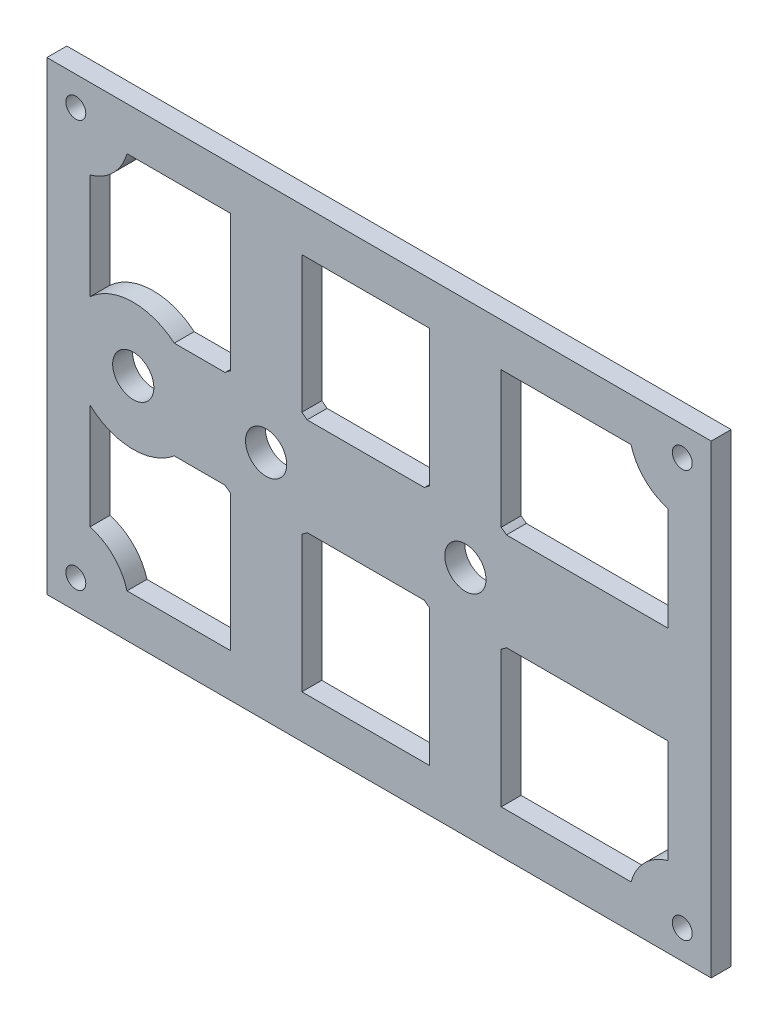
SolidWorks part; units mm, degrees
ref_plane "Front Plane" through (0, 0, 0) normal (0, 0, 1) x (1, 0, 0)
ref_plane "Top Plane" through (0, 0, 0) normal (0, 1, 0) x (1, 0, 0)
ref_plane "Right Plane" through (0, 0, 0) normal (1, 0, 0) x (0, 0, -1)
sketch "Sketch1" plane through (0, 0, 0) normal (0, 0, 1) x (1, 0, 0)
  line L1 (50, -35) -> (-50, -35)
  line L2 (50, -35) -> (50, 35)
  line L3 (50, 35) -> (-50, 35)
  line L4 (-50, -35) -> (-50, 35)
  line L5 (50, -35) -> (-50, 35) construction
  line L6 (50, 35) -> (-50, -35) construction
  point P0 (0, 0)
  dimension "D1" = 70
  dimension "D2" = 100
extrude "Boss-Extrude1" add sketch "Sketch1" along normal blind 3
sketch "Sketch2" plane through (0, 0, 3) normal (0, 0, 1) x (1, 0, 0)
  line L0 (-50, 35) -> (-50, -35) construction
  circle A0 centre (-17, 0) radius 3.1
  circle A1 centre (-37, 0) radius 3.1
  circle A2 centre (13, 0) radius 3.1
  dimension "D1" = 6.2
  dimension "D2" = 20
  dimension "D3" = 30
  dimension "D4" = 13
extrude "Cut-Extrude1" cut sketch "Sketch2" against normal through all
sketch "Sketch3" plane through (0, 0, 3) normal (0, 0, 1) x (1, 0, 0)
  line L0 (-50, 35) -> (-36.9943, 21.9943) construction
  circle A0 centre (-45.6446, 30.6446) radius 1.5
  dimension "D1" = 3
extrude "Cut-Extrude2" cut sketch "Sketch3" against normal through all
mirror "Mirror1" about plane through (0, 0, 0) normal (1, 0, 0) of "Cut-Extrude2"
mirror "Mirror2" about plane through (0, 0, 0) normal (0, 1, 0) of "Mirror1", "Cut-Extrude2"
sketch "Sketch4" plane through (0, 0, 3) normal (0, 0, 1) x (1, 0, 0)
  line L0 (7.6134, 28.5) -> (-11.6134, 28.5)
  line L1 (43.5, 7.3498) -> (43.5, 22.9374)
  line L2 (19.1758, -7.3498) -> (43.5, -7.3498)
  line L3 (18.3866, -28.5) -> (37.9374, -28.5)
  line L4 (-22.3866, 28.5) -> (-37.9374, 28.5)
  line L8 (-43.5, 28.5) -> (-43.5, -28.5)
  line L9 (-43.5, -28.5) -> (43.5, -28.5)
  line L10 (43.5, -28.5) -> (43.5, 28.5)
  line L11 (43.5, 28.5) -> (-43.5, 28.5)
  line L12 (-43.5, 22.9374) -> (-43.5, 7.0647)
  line L13 (-37.9374, -28.5) -> (-22.3866, -28.5)
  line L14 (43.5, -22.9374) -> (43.5, -7.3498)
  line L15 (37.9374, 28.5) -> (18.3866, 28.5)
  line L17 (-11.6134, -28.5) -> (7.6134, -28.5)
  line L18 (-17, 33.7741) -> (-17, -30.6446) construction
  line L20 (-11.6134, -28.5) -> (-11.6134, -7.9464)
  line L22 (-22.3866, -28.5) -> (-22.3866, -7.9464)
  line L23 (13, 30.6446) -> (13, -30.6446) construction
  line L24 (-46.714, 0) -> (46.9945, 0) construction
  line L26 (18.3866, -28.5) -> (18.3866, -7.9464)
  line L28 (7.6134, -28.5) -> (7.6134, -7.9464)
  line L29 (-43.5, -7.0647) -> (-43.5, -22.9374)
  line L30 (-10.8242, -7.3498) -> (6.8242, -7.3498)
  line L31 (-30.8242, 7.3498) -> (-23.1758, 7.3498)
  line L33 (-30.8242, -7.3498) -> (-23.1758, -7.3498)
  line L36 (-22.3866, 7.9464) -> (-22.3866, 28.5)
  line L37 (-11.6134, 7.9464) -> (-11.6134, 28.5)
  line L38 (-10.8242, 7.3498) -> (6.8242, 7.3498)
  line L40 (7.6134, 7.9464) -> (7.6134, 28.5)
  line L43 (18.3866, 7.9464) -> (18.3866, 28.5)
  line L44 (19.1758, 7.3498) -> (43.5, 7.3498)
  arc A0 (18.3866, -7.9464) -> (19.1758, -7.3498) centre (13, 0) ccw
  arc A1 (-23.1758, -7.3498) -> (-22.3866, -7.9464) centre (-17, 0) ccw
  arc A2 (-11.6134, -7.9464) -> (-10.8242, -7.3498) centre (-17, 0) ccw
  circle A3 centre (-45.6446, 30.6446) radius 8
  arc A4 (-43.5, 22.9374) -> (-37.9374, 28.5) centre (-45.6446, 30.6446) ccw
  arc A5 (-30.8242, 7.3498) -> (-43.5, 7.0647) centre (-37, 0) ccw
  circle A6 centre (-37, 0) radius 9.6
  arc A8 (-43.5, -7.0647) -> (-30.8242, -7.3498) centre (-37, 0) ccw
  circle A12 centre (-17, 0) radius 9.6
  arc A13 (-22.3866, 7.9464) -> (-23.1758, 7.3498) centre (-17, 0) ccw
  circle A15 centre (13, 0) radius 9.6
  arc A16 (6.8242, -7.3498) -> (7.6134, -7.9464) centre (13, 0) ccw
  circle A18 centre (45.6446, -30.6446) radius 8
  arc A19 (43.5, -22.9374) -> (37.9374, -28.5) centre (45.6446, -30.6446) ccw
  arc A20 (-10.8242, 7.3498) -> (-11.6134, 7.9464) centre (-17, 0) ccw
  circle A21 centre (45.6446, 30.6446) radius 8
  arc A22 (37.9374, 28.5) -> (43.5, 22.9374) centre (45.6446, 30.6446) ccw
  arc A23 (19.1758, 7.3498) -> (18.3866, 7.9464) centre (13, 0) ccw
  arc A25 (7.6134, 7.9464) -> (6.8242, 7.3498) centre (13, 0) ccw
  circle A26 centre (-45.6446, -30.6446) radius 8
  arc A27 (-37.9374, -28.5) -> (-43.5, -22.9374) centre (-45.6446, -30.6446) ccw
  dimension "D9" = 6.5
  dimension "D3" = 20.5536
  dimension "D10" = 7.6484
  dimension "D1" = 6.5
  dimension "D2" = 6.5
  dimension "D4" = 6.5
  dimension "D5" = 6.5
  dimension "D6" = 6.5
  dimension "D7" = 6.5
  dimension "D8" = 6.5
extrude "Cut-Extrude3" cut sketch "Sketch4" against normal through all
